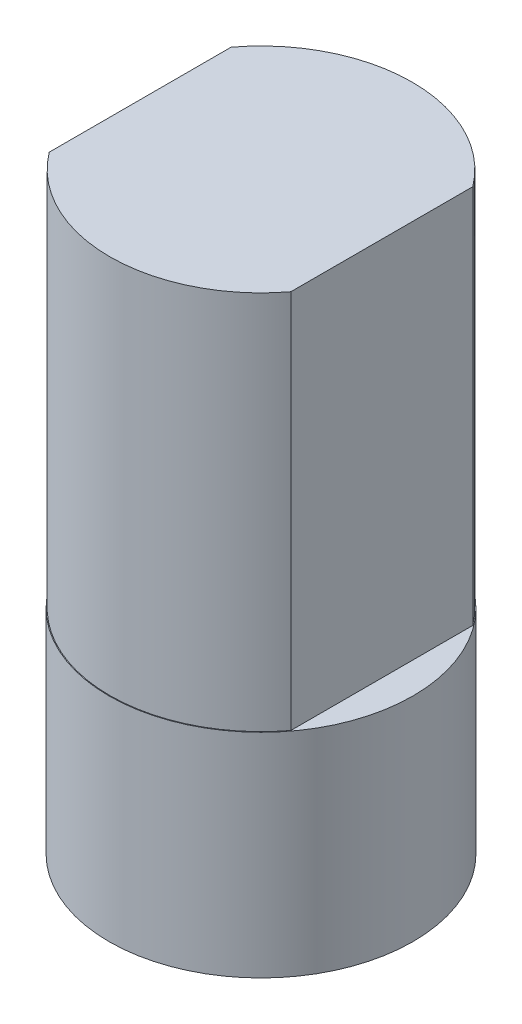
SolidWorks part; units mm, degrees
ref_plane "Front Plane" through (0, 0, 0) normal (0, 0, 1) x (1, 0, 0)
ref_plane "Top Plane" through (0, 0, 0) normal (0, 1, 0) x (1, 0, 0)
ref_plane "Right Plane" through (0, 0, 0) normal (1, 0, 0) x (0, 0, -1)
sketch "Sketch2" plane through (0, 0, 0) normal (0, 1, 0) x (1, 0, 0)
  circle A0 centre (0, 0) radius 5
  dimension "D1" = 10
extrude "Boss-Extrude1" add sketch "Sketch2" along normal blind 7
sketch "Sketch3" plane through (0, 7, 0) normal (0, 1, 0) x (1, 0, 0)
  line L2 (-3.975, 2.9917) -> (-3.975, -2.9917)
  line L4 (3.975, 2.9917) -> (3.975, -2.9917)
  line L5 (-3.975, 5.437) -> (3.975, -5.437) construction
  line L6 (-3.975, -5.437) -> (3.975, 5.437) construction
  arc A0 (-3.975, -2.9917) -> (3.975, -2.9917) centre (0, 0) ccw
  arc A1 (3.975, 2.9917) -> (-3.975, 2.9917) centre (0, 0) ccw
  point P7 (-4.975, 0)
  dimension "D1" = 9.95
  dimension "D2" = 1
extrude "Boss-Extrude2" add sketch "Sketch3" along normal blind 12.5
